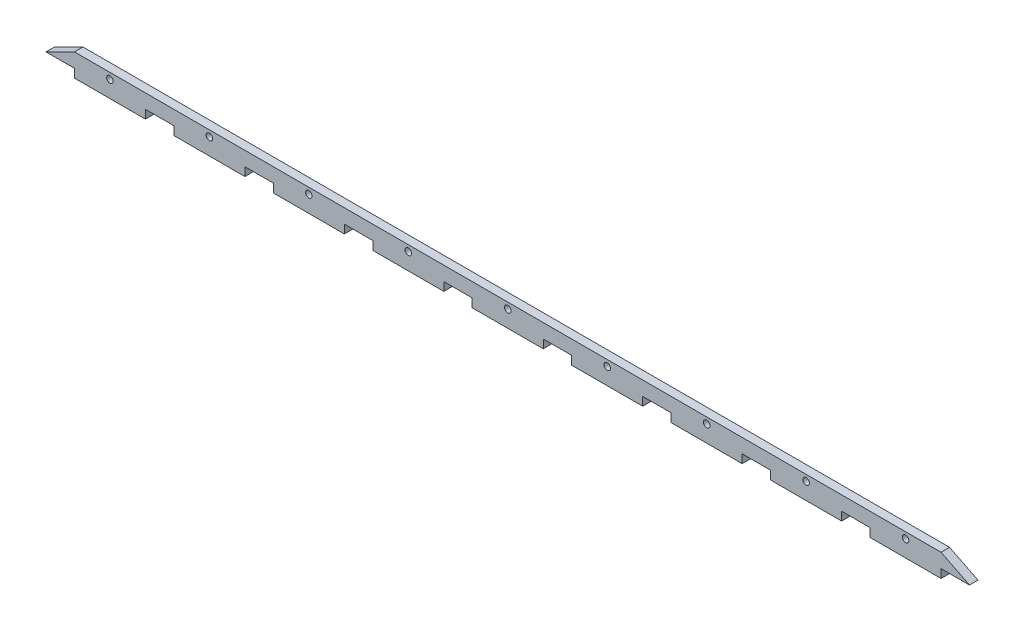
SolidWorks part; units mm, degrees
material "Thornel Mat VMA"
ref_plane "前视基准面" through (0, 0, 0) normal (0, 0, 1) x (1, 0, 0)
ref_plane "上视基准面" through (0, 0, 0) normal (0, 1, 0) x (1, 0, 0)
ref_plane "右视基准面" through (0, 0, 0) normal (1, 0, 0) x (0, 0, -1)
sketch "草图1" plane through (0, 0, 0) normal (0, 0, 1) x (1, 0, 0)
  line L0 (0, 0) -> (10, 5)
  line L1 (10, 5) -> (315, 5)
  line L3 (0, 0) -> (10, 0)
  line L4 (10, 0) -> (10, -3)
  line L5 (10, -3) -> (35, -3)
  line L6 (35, -3) -> (35, 0)
  line L7 (35, 0) -> (45, 0)
  line L8 (45, 0) -> (45, -3)
  line L9 (45, -3) -> (70, -3)
  line L10 (70, -3) -> (70, 0)
  line L11 (70, 0) -> (80, 0)
  line L12 (80, 0) -> (80, -3)
  line L13 (80, -3) -> (105, -3)
  line L14 (105, -3) -> (105, 0)
  line L15 (105, 0) -> (115, 0)
  line L16 (115, 0) -> (115, -3)
  line L17 (115, -3) -> (140, -3)
  line L18 (140, -3) -> (140, 0)
  line L19 (140, 0) -> (150, 0)
  line L20 (150, 0) -> (150, -3)
  line L21 (150, -3) -> (175, -3)
  line L22 (175, -3) -> (175, 0)
  line L23 (175, 0) -> (185, 0)
  line L24 (185, 0) -> (185, -3)
  line L25 (185, -3) -> (210, -3)
  line L26 (210, -3) -> (210, 0)
  line L27 (210, 0) -> (220, 0)
  line L28 (220, 0) -> (220, -3)
  line L29 (220, -3) -> (245, -3)
  line L30 (245, -3) -> (245, 0)
  line L31 (245, 0) -> (255, 0)
  line L32 (255, 0) -> (255, -3)
  line L33 (255, -3) -> (280, -3)
  line L34 (280, -3) -> (280, 0)
  line L36 (280, 0) -> (290, 0)
  line L37 (290, 0) -> (290, -3)
  line L38 (290, -3) -> (315, -3)
  line L39 (315, -3) -> (315, 0) [skipped]
  line L40 (290, -3) -> (315, -3) [skipped]
  line L41 (290, 0) -> (290, -3) [skipped]
  line L42 (280, 0) -> (290, 0) [skipped]
  line L43 (315, -3) -> (315, 0)
  line L44 (315, 0) -> (325, 0)
  line L45 (325, 0) -> (315, 5)
  dimension "D1" = 25
  dimension "D2" = 10
  dimension "D3" = 25
  dimension "D4" = 3
  dimension "D6" = 5
  dimension "D7" = 10
  dimension "D8" = 10
  dimension "D9" = 3
  dimension "D5" = 9
extrude "凸台-拉伸1" add sketch "草图1" along normal blind 3
sketch "草图2" plane through (0, 0, 3) normal (0, 0, 1) x (1, 0, 0)
  line L0 (22.5, -3) -> (22.5, 5) construction
  line L1 (10, -3) -> (35, -3) construction
  line L2 (315, 5) -> (10, 5) construction
  line L3 (57.5, -3) -> (57.5, 5) construction
  line L4 (92.5, -3) -> (92.5, 5) construction
  line L5 (127.5, -3) -> (127.5, 5) construction
  line L6 (162.5, -3) -> (162.5, 5) construction
  line L7 (197.5, -3) -> (197.5, 5) construction
  line L8 (232.5, -3) -> (232.5, 5) construction
  line L9 (267.5, -3) -> (267.5, 5) construction
  line L10 (302.5, -3) -> (302.5, 5) construction
  circle A0 centre (22.5, 2.85) radius 1.15
  circle A1 centre (57.5, 2.85) radius 1.15
  circle A2 centre (92.5, 2.85) radius 1.15
  circle A3 centre (127.5, 2.85) radius 1.15
  circle A4 centre (162.5, 2.85) radius 1.15
  circle A5 centre (197.5, 2.85) radius 1.15
  circle A6 centre (232.5, 2.85) radius 1.15
  circle A7 centre (267.5, 2.85) radius 1.15
  circle A8 centre (302.5, 2.85) radius 1.15
  dimension "D1" = 2.3
  dimension "D2" = 2.15
  dimension "D4" = 35
  dimension "D3" = 9
extrude "切除-拉伸1" cut sketch "草图2" against normal through all
